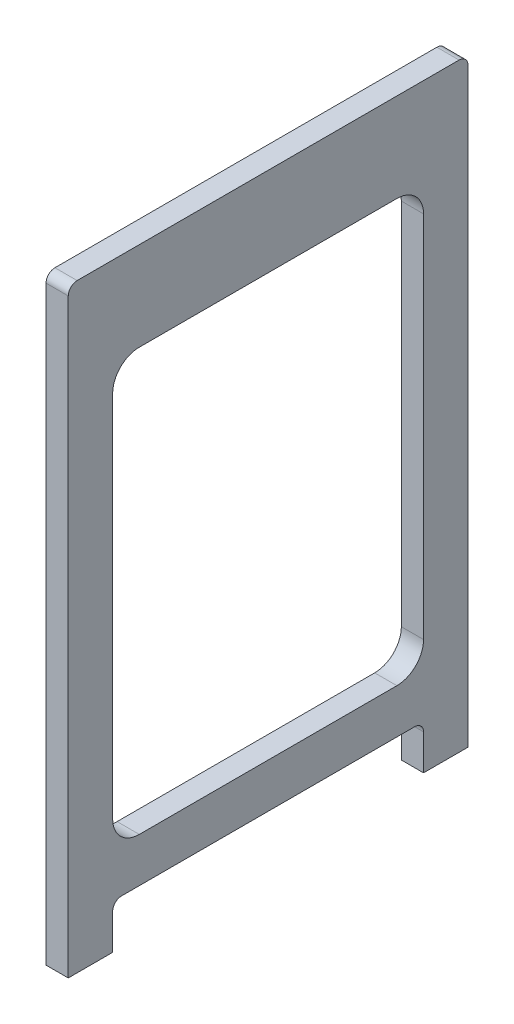
SolidWorks part; units mm, degrees
material "Teak"
ref_plane "Front Plane" through (0, 0, 0) normal (0, 0, 1) x (1, 0, 0)
ref_plane "Top Plane" through (0, 0, 0) normal (0, 1, 0) x (1, 0, 0)
ref_plane "Right Plane" through (0, 0, 0) normal (1, 0, 0) x (0, 0, -1)
sketch "Sketch1" plane through (0, 0, 0) normal (1, 0, 0) x (0, 0, -1)
  line L0 (-175, -337.5) -> (-225, -337.5)
  line L1 (225, -337.5) -> (175, -337.5)
  line L2 (225, -337.5) -> (225, 337.5)
  line L3 (225, 337.5) -> (-225, 337.5)
  line L4 (-225, -337.5) -> (-225, 337.5)
  line L5 (225, -337.5) -> (-225, 337.5) construction
  line L6 (225, 337.5) -> (-225, -337.5) construction
  line L7 (175, -237.5) -> (-175, -237.5)
  line L8 (175, -237.5) -> (175, 237.5)
  line L9 (175, 237.5) -> (-175, 237.5)
  line L10 (-175, -237.5) -> (-175, 237.5)
  line L11 (175, -237.5) -> (-175, 237.5) construction
  line L12 (175, 237.5) -> (-175, -237.5) construction
  line L13 (-225, 330) -> (225, 330) construction
  line L14 (-175, -337.5) -> (-175, -287.5)
  line L15 (-175, -287.5) -> (175, -287.5)
  line L16 (175, -337.5) -> (175, -287.5)
  line L17 (0, 337.5) -> (0, 0) construction
  circle A0 centre (-150, 330) radius 2.5
  circle A1 centre (-110, 330) radius 2.5
  circle A2 centre (-130, 315) radius 2.5
  circle A3 centre (110, 330) radius 2.5
  circle A4 centre (150, 330) radius 2.5
  circle A5 centre (130, 315) radius 2.5
  point P0 (0, 0)
  point P6 (0, 0)
  dimension "D11" = 5
  dimension "D1" = 450
  dimension "D2" = 675
  dimension "D3" = 50
  dimension "D4" = 50
  dimension "D5" = 50
  dimension "D6" = 50
  dimension "D7" = 7.5
  dimension "D8" = 15
  dimension "D9" = 20
  dimension "D10" = 40
  dimension "D12" = 75
extrude "Boss-Extrude1" add sketch "Sketch1" along normal mid plane 25
sketch "Sketch2" plane through (12.5, 0, 0) normal (1, 0, 0) x (0, 0, -1)
  circle A0 centre (-110, 330) radius 2.5 construction
  circle A1 centre (-130, 315) radius 2.5 construction
  circle A2 centre (-150, 330) radius 2.5 construction
  circle A3 centre (-110, 330) radius 2.5
  circle A4 centre (-130, 315) radius 2.5
  circle A5 centre (-150, 330) radius 2.5
  circle A6 centre (150, 330) radius 2.5 construction
  circle A7 centre (130, 315) radius 2.5 construction
  circle A8 centre (110, 330) radius 2.5 construction
  circle A9 centre (150, 330) radius 2.5
  circle A10 centre (130, 315) radius 2.5
  circle A11 centre (110, 330) radius 2.5
extrude "Boss-Extrude2" add sketch "Sketch2" against normal blind 15
fillet "Fillet1" radius 10 2 edges at (0, -287.5, -175) (0, -287.5, 175)
fillet "Fillet2" radius 30 4 edges at (0, 237.5, 175) (0, 237.5, -175) (0, -237.5, -175) (0, -237.5, 175)
fillet "Fillet3" radius 10 2 edges at (0, 337.5, -225) (0, 337.5, 225)
